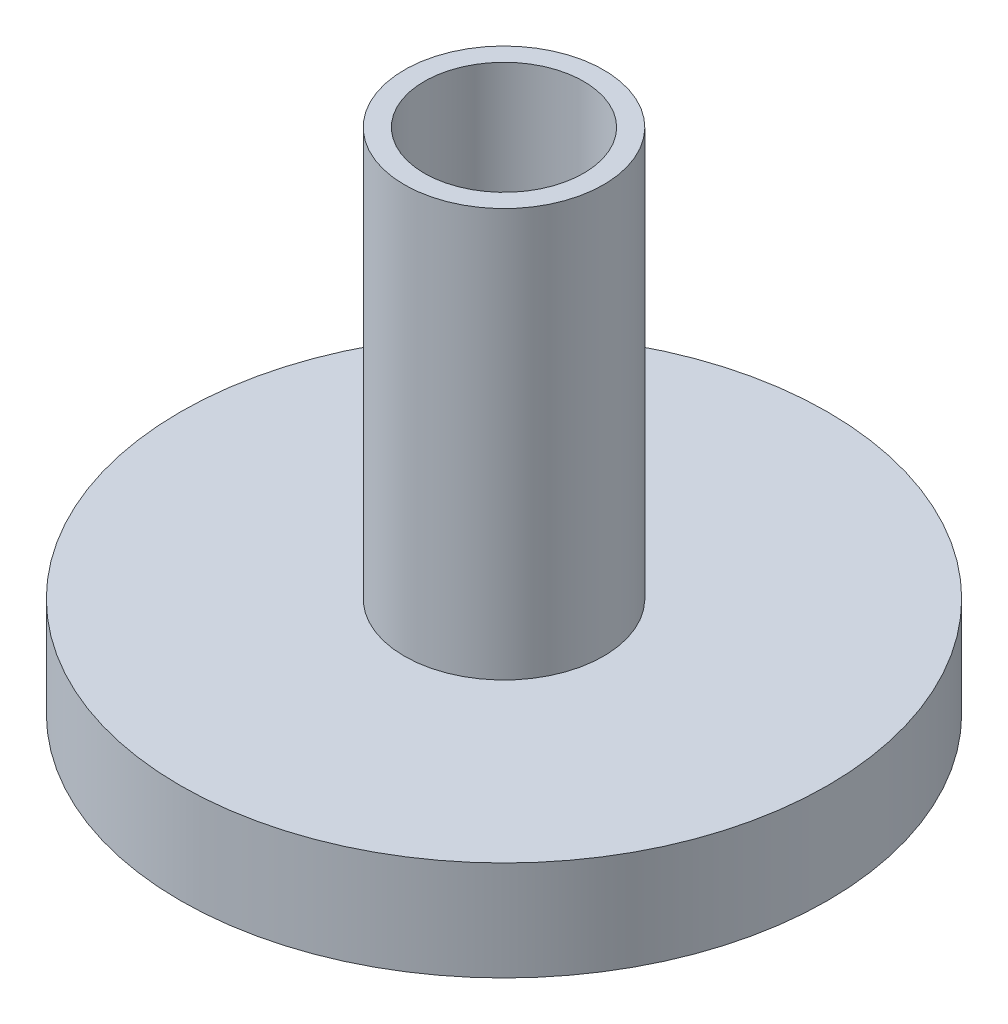
SolidWorks part; units mm, degrees
ref_plane "Front Plane" through (0, 0, 0) normal (0, 0, 1) x (1, 0, 0)
ref_plane "Top Plane" through (0, 0, 0) normal (0, 1, 0) x (1, 0, 0)
ref_plane "Right Plane" through (0, 0, 0) normal (1, 0, 0) x (0, 0, -1)
sketch "Sketch1" plane through (0, 0, 0) normal (0, 1, 0) x (1, 0, 0)
  circle A0 centre (0, 0) radius 6.35
  circle A1 centre (0, 0) radius 5.08
  dimension "D1" = 12.7
  dimension "D2" = 1.27
extrude "Boss-Extrude1" add sketch "Sketch1" along normal blind 26.035
sketch "Sketch2" plane through (0, 0, 0) normal (0, -1, 0) x (1, 0, 0)
  circle A0 centre (0, 0) radius 20.6375
  dimension "D1" = 41.275
extrude "Boss-Extrude2" add sketch "Sketch2" along normal blind 6.35
sketch "Sketch3" plane through (0, 0, 0) normal (0, 1, 0) x (1, 0, 0)
  circle A0 centre (0, 0) radius 5.08
extrude "Boss-Extrude3" add sketch "Sketch3" along normal offset from surface (15.875 mm away) 10.16 up to face at (0, 26.035, 6.35)
